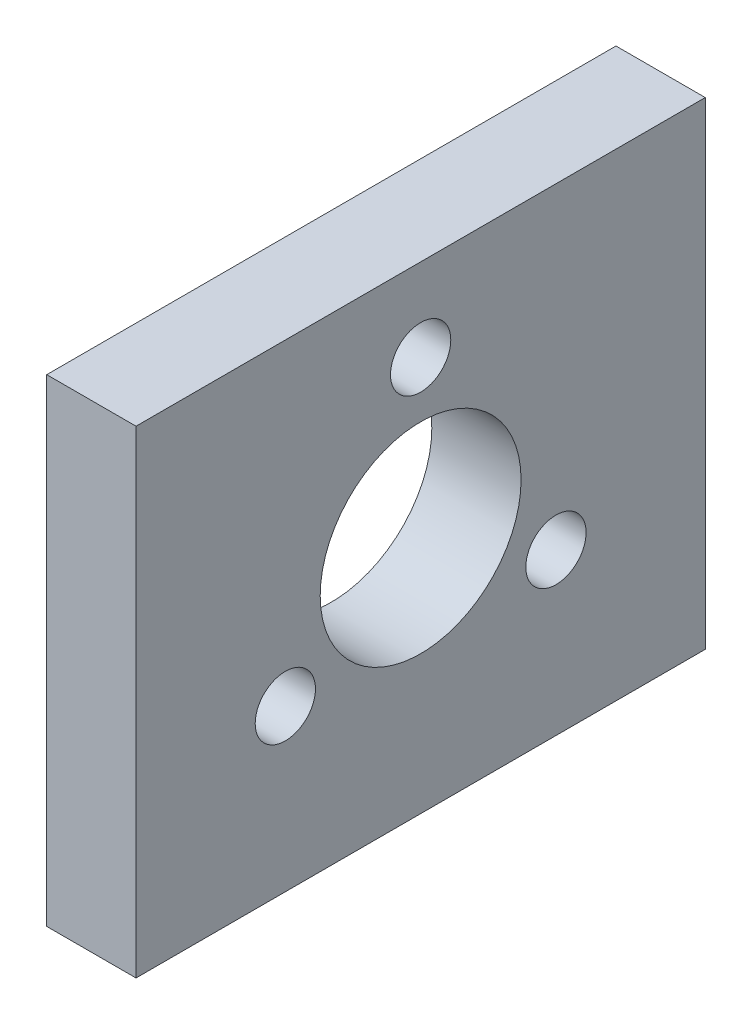
SolidWorks part; units mm, degrees
ref_plane "Front Plane" through (0, 0, 0) normal (0, 0, 1) x (1, 0, 0)
ref_plane "Top Plane" through (0, 0, 0) normal (0, 1, 0) x (1, 0, 0)
ref_plane "Right Plane" through (0, 0, 0) normal (1, 0, 0) x (0, 0, -1)
sketch "Sketch2" plane through (0, 0, 0) normal (1, 0, 0) x (0, 0, -1)
  line L1 (12.7512, -10.7048) -> (-12.7512, -10.7048)
  line L2 (12.7512, -10.7048) -> (12.7512, 10.7048)
  line L3 (12.7512, 10.7048) -> (-12.7512, 10.7048)
  line L4 (-12.7512, -10.7048) -> (-12.7512, 10.7048)
  line L5 (12.7512, -10.7048) -> (-12.7512, 10.7048) construction
  line L6 (12.7512, 10.7048) -> (-12.7512, -10.7048) construction
  point P0 (0, 0)
  point P6 (0, 7)
  point P10 (6.0622, -3.5)
  point P11 (-6.0622, -3.5)
  point P12 (0, 0)
  dimension "D1" = 7
  dimension "D2" = 3
extrude "Boss-Extrude1" add sketch "Sketch2" along normal blind 4
sketch "Sketch3" plane through (0, 0, 0) normal (-1, 0, 0) x (0, 0, 1)
  point P0 (0, 7)
  point P1 (6.0622, -3.5)
  point P5 (-6.0622, -3.5)
  point P6 (0, 0)
  dimension "D1" = 7
  dimension "D2" = 3
hole_wizard "M2.5 Clearance Hole1" positions "Sketch5" profile "Sketch4" hole size "M2.5" standard "ANSI Metric"
sketch "Sketch5" plane through (0, 0, 0) normal (-1, 0, 0) x (0, 0, 1)
  point P0 (0, 7)
  point P3 (-6.0622, -3.5)
  point P6 (6.0622, -3.5)
sketch "Sketch4" plane through (0, 7, 0) normal (0, 1, 0) x (0, 0, 1)
  line L0 (0, 0) -> (0, 7.4612)
  line L1 (0, 7.4612) -> (1.35, 6.65)
  line L2 (1.35, 6.65) -> (1.35, 0)
  line L5 (1.35, 0) -> (0, 0)
  line L10 (0, 7.4612) -> (-1.35, 6.65) construction
  line L11 (0, -6.35) -> (0, 107.95) construction
  dimension "Hole Dia." = 2.7
  dimension "Hole Depth" = 6.65
  dimension "Drill Angle" = 118
sketch "Sketch6" plane through (0, 0, 0) normal (-1, 0, 0) x (0, 0, 1)
  circle A0 centre (0, 0) radius 4.5
  dimension "D1" = 9
extrude "Cut-Extrude1" cut sketch "Sketch6" against normal through all
